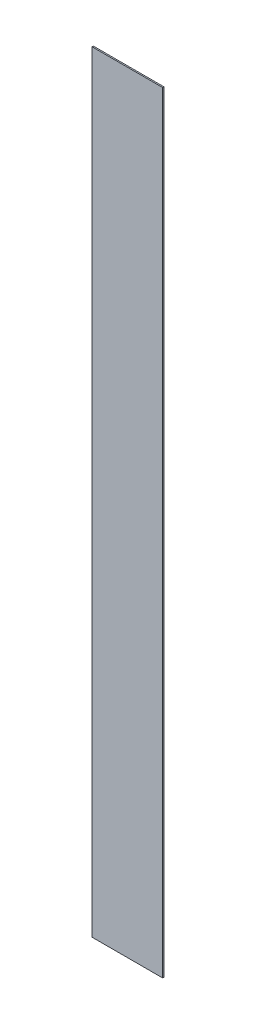
SolidWorks part; units mm, degrees
ref_plane "Front Plane" through (0, 0, 0) normal (0, 0, 1) x (1, 0, 0)
ref_plane "Top Plane" through (0, 0, 0) normal (0, 1, 0) x (1, 0, 0)
ref_plane "Right Plane" through (0, 0, 0) normal (1, 0, 0) x (0, 0, -1)
other "Configuration Table"
sketch "Sketch1" plane through (0, 0, 0) normal (0, 0, 1) x (1, 0, 0)
  line L1 (497.5, 300) -> (607.5, 300)
  line L2 (497.5, 300) -> (497.5, 1500)
  line L3 (497.5, 1500) -> (607.5, 1500)
  line L4 (607.5, 300) -> (607.5, 1500)
extrude "TOPPING_sag_kanal_hava_donus_izgarasi_1" add sketch "Sketch1" against normal blind 2 from offset 18 separate body
